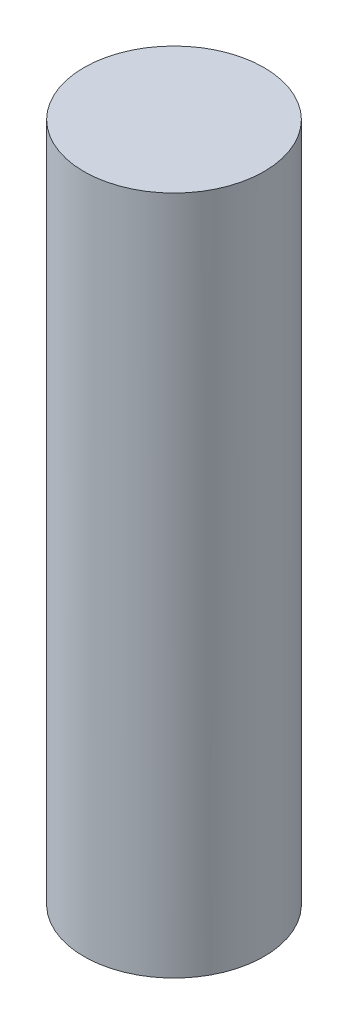
SolidWorks part; units mm, degrees
ref_plane "Front Plane" through (0, 0, 0) normal (0, 0, 1) x (1, 0, 0)
ref_plane "Top Plane" through (0, 0, 0) normal (0, 1, 0) x (1, 0, 0)
ref_plane "Right Plane" through (0, 0, 0) normal (1, 0, 0) x (0, 0, -1)
sketch "Sketch1" plane through (0, 0, 0) normal (0, 1, 0) x (1, 0, 0)
  circle A0 centre (0, 0) radius 13.25
  dimension "2.65" = 26.5
extrude "Boss-Extrude1" add sketch "Sketch1" along normal blind 100
sketch "Sketch2" plane through (0, 0, 0) normal (0, 0, 1) x (1, 0, 0)
  line L0 (0, -3) -> (0, 8.9661) construction
  line L1 (-13.25, 0) -> (13.25, 0) construction
  line L2 (0, -3) -> (0, 0.4422)
  line L3 (13.25, 0) -> (0, 0.4422)
  arc A0 (0, -3) -> (13.25, 0) centre (0, 27.7604) ccw
  dimension "D1" = 3
revolve "Revolve1" add sketch "Sketch2" angle 360 about L0
